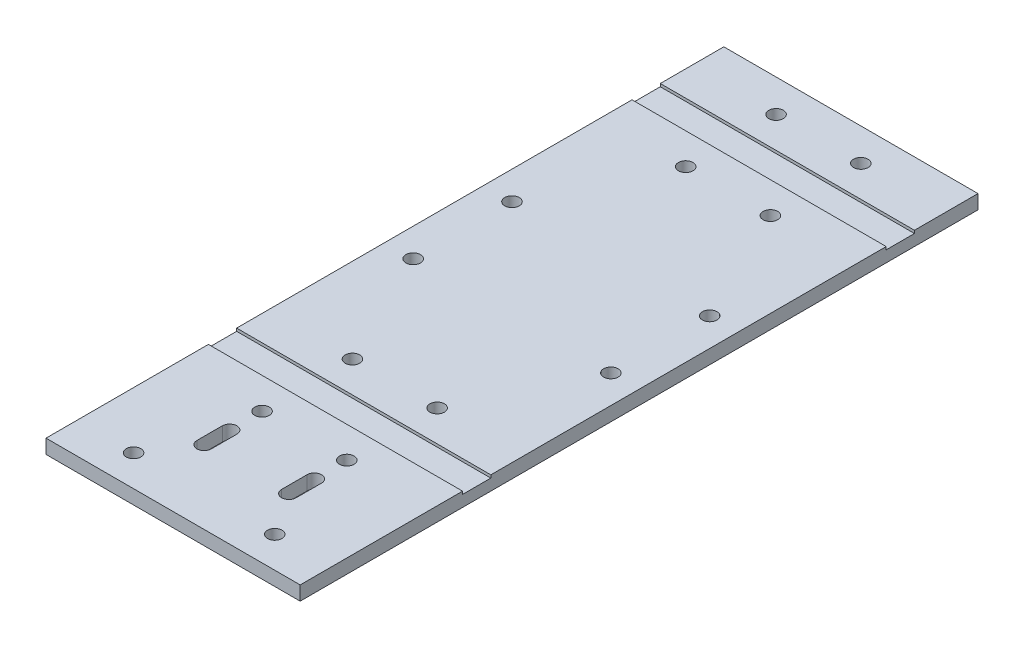
SolidWorks part; units mm, degrees
ref_plane "Front Plane" through (0, 0, 0) normal (0, 0, 1) x (1, 0, 0)
ref_plane "Top Plane" through (0, 0, 0) normal (0, 1, 0) x (1, 0, 0)
ref_plane "Right Plane" through (0, 0, 0) normal (1, 0, 0) x (0, 0, -1)
sketch "Sketch1" plane through (0, 0, 0) normal (0, 0, 1) x (1, 0, 0)
  line L1 (-22.5, -2.5) -> (22.5, -2.5)
  line L2 (-22.5, -2.5) -> (-22.5, 2.5)
  line L3 (-22.5, 2.5) -> (22.5, 2.5)
  line L4 (22.5, -2.5) -> (22.5, 2.5)
  line L5 (-22.5, -2.5) -> (22.5, 2.5) construction
  line L6 (-22.5, 2.5) -> (22.5, -2.5) construction
  point P0 (0, 0)
  dimension "D1" = 45
  dimension "D2" = 5
extrude "Boss-Extrude1" add sketch "Sketch1" along normal blind 102.5
ref_plane "Plane1" through (0, 0, 75) normal (0, 0, 1) x (1, 0, 0)
sketch "Sketch2" plane through (0, 2.5, 0) normal (0, 1, 0) x (1, 0, 0)
  line L0 (-2.75, -75) -> (2.75, -75) construction
  line L1 (-22.5, -102.5) -> (-22.5, 0) construction
  circle A0 centre (-15, -59) radius 2.575
  circle A1 centre (15, -59) radius 2.575
  circle A2 centre (-15, -91) radius 2.575
  circle A3 centre (15, -91) radius 2.575
  dimension "D3" = 5.15
  dimension "D4" = 30
  dimension "D5" = 7.5
  dimension "D1" = 16
  dimension "D2" = 16
extrude "Cut-Extrude1" cut sketch "Sketch2" against normal through all
sketch "Sketch3" plane through (22.5, 0, 0) normal (1, 0, 0) x (0, 0, -1)
  line L0 (-102.5, 2.5) -> (0, 2.5) construction
  line L1 (-70, 2.5) -> (-80, 2.5)
  line L2 (-70, 2.5) -> (-70, 1.5)
  line L3 (-70, 1.5) -> (-80, 1.5)
  line L4 (-80, 2.5) -> (-80, 1.5)
  line L5 (-75, 2.75) -> (-75, -2.75) construction
  point P6 (-75, 1.5)
  dimension "D1" = 10
  dimension "D2" = 1
extrude "Cut-Extrude2" cut sketch "Sketch3" against normal through all
mirror "Mirror1" about plane through (0, 0, 0) normal (0, 0, 1) of "Cut-Extrude2", "Cut-Extrude1", "Boss-Extrude1"
ref_plane "Plane2" through (0, 0, -75) normal (0, 0, 1) x (1, 0, 0)
sketch "Sketch4" plane through (0, 0, 102.5) normal (0, 0, 1) x (1, 0, 0)
  line L4 (22.5, -2.5) -> (22.5, 2.5)
  line L5 (22.5, 2.5) -> (-22.5, 2.5)
  line L6 (-22.5, 2.5) -> (-22.5, -2.5)
  line L7 (-22.5, -2.5) -> (22.5, -2.5)
  line L8 (22.5, -2.5) -> (22.5, 2.5)
  line L9 (22.5, 2.5) -> (-22.5, 2.5)
  line L10 (-22.5, 2.5) -> (-22.5, -2.5)
  line L11 (-22.5, -2.5) -> (22.5, -2.5)
  dimension "D1" = 0
extrude "Boss-Extrude2" add sketch "Sketch4" along normal blind 35
sketch "Sketch5" plane through (22.5, 0, 0) normal (1, 0, 0) x (0, 0, -1)
  line L12 (70, 1.5) -> (70, 2.5)
  line L13 (70, 2.5) -> (-70, 2.5)
  line L14 (-70, 2.5) -> (-70, 1.5)
  line L15 (-70, 1.5) -> (-80, 1.5)
  line L16 (-80, 1.5) -> (-80, 2.5)
  line L17 (-80, 2.5) -> (-137.5, 2.5)
  line L18 (-137.5, 2.5) -> (-137.5, -2.5)
  line L19 (-137.5, -2.5) -> (102.5, -2.5)
  line L20 (102.5, -2.5) -> (102.5, 2.5)
  line L21 (102.5, 2.5) -> (80, 2.5)
  line L22 (80, 2.5) -> (80, 1.5)
  line L23 (80, 1.5) -> (70, 1.5)
  line L24 (70, 1.5) -> (70, 2.5)
  line L25 (70, 2.5) -> (-70, 2.5)
  line L26 (-70, 2.5) -> (-70, 1.5)
  line L27 (-70, 1.5) -> (-80, 1.5)
  line L28 (-80, 1.5) -> (-80, 2.5)
  line L29 (-80, 2.5) -> (-137.5, 2.5)
  line L30 (-137.5, 2.5) -> (-137.5, -2.5)
  line L31 (-137.5, -2.5) -> (102.5, -2.5)
  line L32 (102.5, -2.5) -> (102.5, 2.5)
  line L33 (102.5, 2.5) -> (80, 2.5)
  line L34 (80, 2.5) -> (80, 1.5)
  line L35 (80, 1.5) -> (70, 1.5)
  dimension "D1" = 0
extrude "Boss-Extrude3" add sketch "Sketch5" along normal blind 22.5
mirror "Mirror2" about plane through (0, 0, 0) normal (1, 0, 0) of "Boss-Extrude3"
sketch "Sketch6" plane through (0, 2.5, 0) normal (0, 1, 0) x (1, 0, 0)
  line L0 (-2.75, 0) -> (2.75, 0) construction
  line L1 (-45, 70) -> (-45, -70) construction
  circle A0 centre (-35, -17.5) radius 2.575
  circle A1 centre (-35, 17.5) radius 2.575
  dimension "D1" = 5.15
  dimension "D2" = 5.15
  dimension "D3" = 17.5
  dimension "D4" = 17.5
  dimension "D5" = 10
extrude "Cut-Extrude3" cut sketch "Sketch6" against normal through all
mirror "Mirror3" about plane through (0, 0, 0) normal (1, 0, 0) of "Cut-Extrude3"
sketch "Sketch7" plane through (0, 2.5, 0) normal (0, 1, 0) x (1, 0, 0)
  line L0 (0, -2.75) -> (0, 2.75) construction
  line L1 (45, -137.5) -> (-45, -137.5) construction
  circle A0 centre (-25, -126.5) radius 2.575
  circle A3 centre (25, -126.5) radius 2.575
  dimension "D1" = 5.15
  dimension "D6" = 25
  dimension "D5" = 11
extrude "Cut-Extrude4" cut sketch "Sketch7" against normal through all
sketch "Sketch8" plane through (0, 2.5, 0) normal (0, 1, 0) x (1, 0, 0)
  line L1 (-15, -111.5) -> (-15, -102.5) construction
  line L2 (-17.575, -111.5) -> (-17.575, -102.5)
  line L3 (-12.425, -111.5) -> (-12.425, -102.5)
  line L4 (0, -2.75) -> (0, 2.75) construction
  line L5 (15, -111.5) -> (15, -102.5) construction
  line L6 (17.575, -111.5) -> (17.575, -102.5)
  line L7 (12.425, -111.5) -> (12.425, -102.5)
  arc A3 (-17.575, -111.5) -> (-12.425, -111.5) centre (-15, -111.5) ccw
  arc A4 (-12.425, -102.5) -> (-17.575, -102.5) centre (-15, -102.5) ccw
  circle A5 centre (-25, -126.5) radius 2.575 construction
  arc A6 (17.575, -111.5) -> (12.425, -111.5) centre (15, -111.5) cw
  arc A7 (12.425, -102.5) -> (17.575, -102.5) centre (15, -102.5) cw
  point P2 (-15, -107)
  point P13 (15, -107)
  dimension "D1" = 2.575
  dimension "D3" = 15
  dimension "D4" = 15
  dimension "D2" = 9
extrude "Cut-Extrude5" cut sketch "Sketch8" against normal through all
